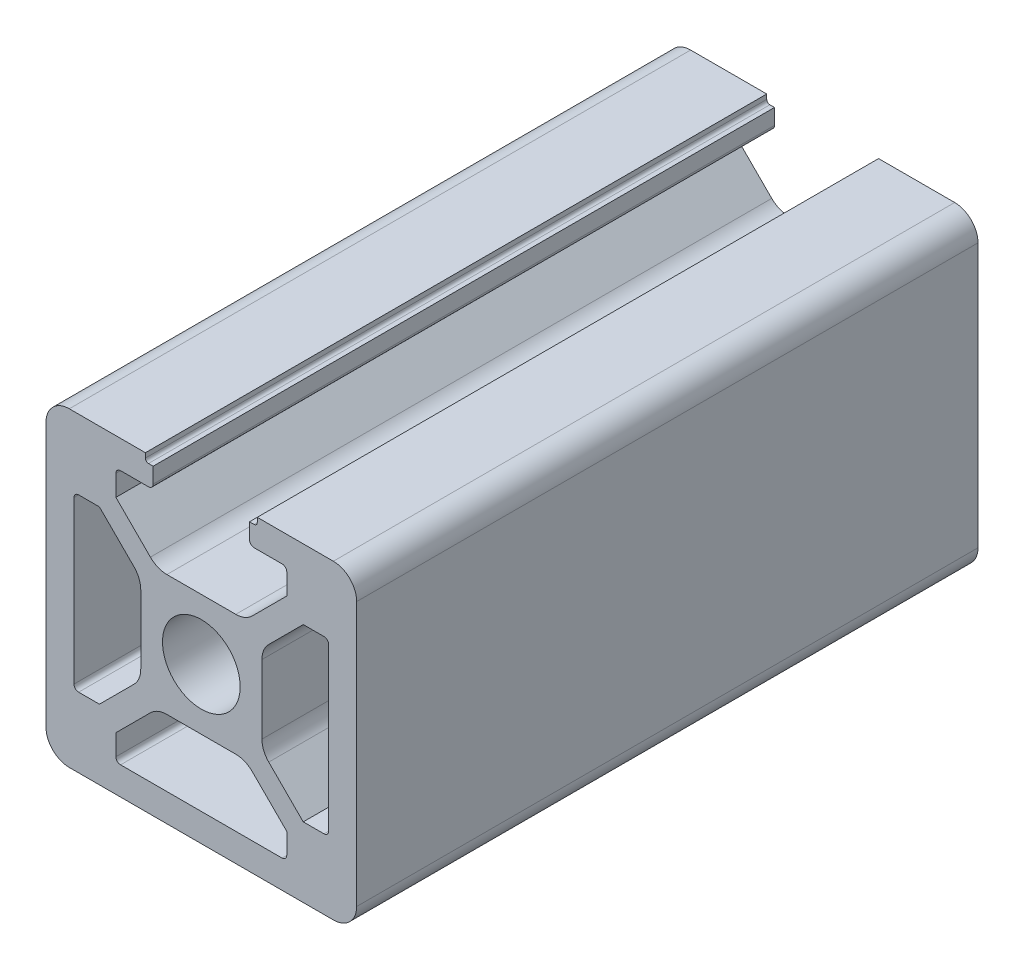
SolidWorks part; units mm, degrees
ref_plane "前视基准面" through (0, 0, 0) normal (0, 0, 1) x (1, 0, 0)
ref_plane "上视基准面" through (0, 0, 0) normal (0, 1, 0) x (1, 0, 0)
ref_plane "右视基准面" through (0, 0, 0) normal (1, 0, 0) x (0, 0, -1)
sketch "草图1" plane through (0, 0, 0) normal (0, 0, 1) x (1, 0, 0)
  line L0 (1598.7341, 639.5053) -> (1600.9548, 641.726)
  line L1 (1600.9548, 641.726) -> (1602.2948, 641.726)
  line L2 (1604.3948, 627.726) -> (1604.3948, 644.726)
  line L3 (1602.8948, 646.226) -> (1597.9948, 646.226)
  line L4 (1597.9948, 646.226) -> (1597.9948, 645.926)
  line L5 (1597.7948, 645.726) -> (1597.4948, 645.726)
  line L6 (1597.4948, 645.726) -> (1597.4948, 644.726)
  line L7 (1597.7948, 644.426) -> (1599.5948, 644.426)
  line L8 (1599.8948, 644.126) -> (1599.8948, 642.786)
  line L9 (1599.8948, 642.786) -> (1597.6741, 640.5653)
  line L10 (1596.6135, 640.126) -> (1592.1761, 640.126)
  line L11 (1591.1154, 640.5653) -> (1588.8948, 642.786)
  line L12 (1588.8948, 642.786) -> (1588.8948, 644.126)
  line L13 (1589.1948, 644.426) -> (1590.9948, 644.426)
  line L14 (1591.2948, 644.726) -> (1591.2948, 645.726)
  line L15 (1591.2948, 645.726) -> (1590.9948, 645.726)
  line L16 (1590.7948, 645.926) -> (1590.7948, 646.226)
  line L17 (1590.7948, 646.226) -> (1585.8948, 646.226)
  line L18 (1586.1948, 631.026) -> (1586.1948, 641.426)
  line L19 (1586.4948, 641.726) -> (1587.8348, 641.726)
  line L20 (1587.8348, 641.726) -> (1590.0554, 639.5053)
  line L21 (1590.4948, 638.4447) -> (1590.4948, 634.0073)
  line L22 (1590.0554, 632.9467) -> (1587.8348, 630.726)
  line L23 (1587.8348, 630.726) -> (1586.4948, 630.726)
  line L24 (1584.3948, 644.726) -> (1584.3948, 627.726)
  line L25 (1585.8948, 626.226) -> (1602.8948, 626.226)
  line L26 (1599.5948, 628.026) -> (1589.1948, 628.026)
  line L27 (1588.8948, 628.326) -> (1588.8948, 629.666)
  line L28 (1588.8948, 629.666) -> (1591.1154, 631.8867)
  line L29 (1592.1761, 632.326) -> (1596.6135, 632.326)
  line L30 (1597.6741, 631.8867) -> (1599.8948, 629.666)
  line L31 (1599.8948, 629.666) -> (1599.8948, 628.326)
  line L32 (1602.5948, 641.426) -> (1602.5948, 631.026)
  line L33 (1602.2948, 630.726) -> (1600.9548, 630.726)
  line L34 (1600.9548, 630.726) -> (1598.7341, 632.9467)
  line L35 (1598.2948, 634.0073) -> (1598.2948, 638.4447)
  circle A0 centre (1594.3948, 636.226) radius 2.5
  arc A1 (1604.3948, 644.726) -> (1602.8948, 646.226) centre (1602.8948, 644.726) ccw
  arc A2 (1597.7948, 645.726) -> (1597.9948, 645.926) centre (1597.7948, 645.926) ccw
  arc A3 (1597.4948, 644.726) -> (1597.7948, 644.426) centre (1597.7948, 644.726) ccw
  arc A4 (1599.8948, 644.126) -> (1599.5948, 644.426) centre (1599.5948, 644.126) ccw
  arc A5 (1596.6135, 640.126) -> (1597.6741, 640.5653) centre (1596.6135, 641.626) ccw
  arc A6 (1591.1154, 640.5653) -> (1592.1761, 640.126) centre (1592.1761, 641.626) ccw
  arc A7 (1589.1948, 644.426) -> (1588.8948, 644.126) centre (1589.1948, 644.126) ccw
  arc A8 (1590.9948, 644.426) -> (1591.2948, 644.726) centre (1590.9948, 644.726) ccw
  arc A9 (1590.7948, 645.926) -> (1590.9948, 645.726) centre (1590.9948, 645.926) ccw
  arc A10 (1585.8948, 646.226) -> (1584.3948, 644.726) centre (1585.8948, 644.726) ccw
  arc A11 (1586.4948, 641.726) -> (1586.1948, 641.426) centre (1586.4948, 641.426) ccw
  arc A12 (1590.4948, 638.4447) -> (1590.0554, 639.5053) centre (1588.9948, 638.4447) ccw
  arc A13 (1590.0554, 632.9467) -> (1590.4948, 634.0073) centre (1588.9948, 634.0073) ccw
  arc A14 (1586.1948, 631.026) -> (1586.4948, 630.726) centre (1586.4948, 631.026) ccw
  arc A15 (1584.3948, 627.726) -> (1585.8948, 626.226) centre (1585.8948, 627.726) ccw
  arc A16 (1588.8948, 628.326) -> (1589.1948, 628.026) centre (1589.1948, 628.326) ccw
  arc A17 (1592.1761, 632.326) -> (1591.1154, 631.8867) centre (1592.1761, 630.826) ccw
  arc A18 (1597.6741, 631.8867) -> (1596.6135, 632.326) centre (1596.6135, 630.826) ccw
  arc A19 (1599.5948, 628.026) -> (1599.8948, 628.326) centre (1599.5948, 628.326) ccw
  arc A20 (1602.8948, 626.226) -> (1604.3948, 627.726) centre (1602.8948, 627.726) ccw
  arc A21 (1602.2948, 630.726) -> (1602.5948, 631.026) centre (1602.2948, 631.026) ccw
  arc A22 (1598.2948, 634.0073) -> (1598.7341, 632.9467) centre (1599.7948, 634.0073) ccw
  arc A23 (1598.7341, 639.5053) -> (1598.2948, 638.4447) centre (1599.7948, 638.4447) ccw
  arc A24 (1602.5948, 641.426) -> (1602.2948, 641.726) centre (1602.2948, 641.426) ccw
extrude "凸台-拉伸1" add sketch "草图1" along normal blind 40
